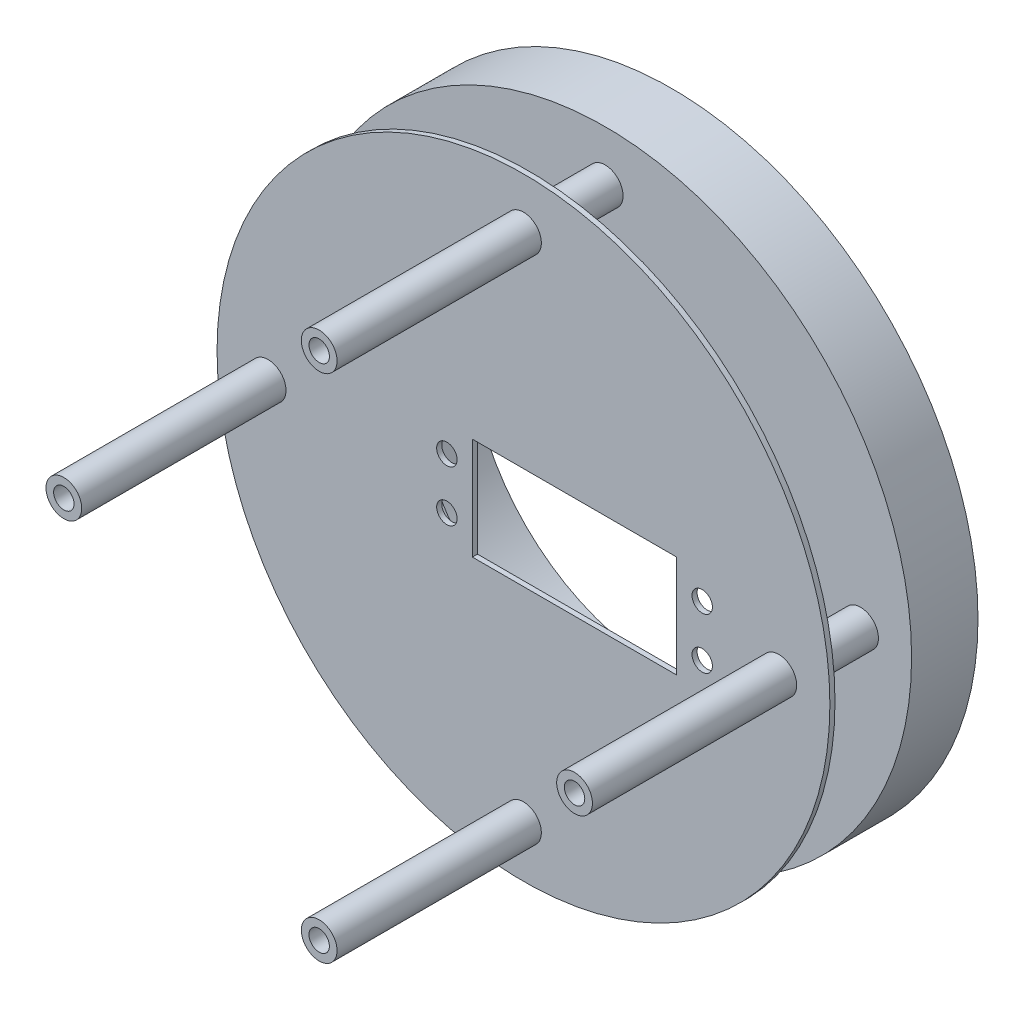
SolidWorks part; units mm, degrees
ref_plane "前视基准面" through (0, 0, 0) normal (0, 0, 1) x (1, 0, 0)
ref_plane "上视基准面" through (0, 0, 0) normal (0, 1, 0) x (1, 0, 0)
ref_plane "右视基准面" through (0, 0, 0) normal (1, 0, 0) x (0, 0, -1)
sketch "草图1" plane through (0, 0, 0) normal (0, 0, 1) x (1, 0, 0)
  circle A0 centre (0, 0) radius 60
  circle A1 centre (0, 0) radius 37.5
  dimension "D1" = 120
  dimension "D2" = 75
extrude "凸台-拉伸1" add sketch "草图1" along normal blind 13
ref_plane "基准面1" through (0, 0, 28) normal (0, 0, 1) x (1, 0, 0)
sketch "草图4" plane through (0, 0, 28) normal (0, 0, 1) x (1, 0, 0)
  line L1 (-10, 10) -> (30, 10)
  line L2 (-10, 10) -> (-10, -10)
  line L3 (-10, -10) -> (30, -10)
  line L4 (30, 10) -> (30, -10)
  circle A0 centre (0, 0) radius 60
  circle A2 centre (-15, 5) radius 2
  circle A3 centre (35, 5) radius 2
  circle A4 centre (35, -5) radius 2
  circle A5 centre (-15, -5) radius 2
  point P7 (-10, 0)
  dimension "D1" = 120
  dimension "D2" = 40
  dimension "D5" = 4
  dimension "D6" = 4
  dimension "D7" = 4
  dimension "D8" = 4
  dimension "D3" = 20
  dimension "D4" = 10
  dimension "D9" = 5
  dimension "D10" = 5
  dimension "D11" = 5
  dimension "D12" = 5
  dimension "D13" = 5
  dimension "D14" = 5
  dimension "D15" = 5
  dimension "D16" = 5
extrude "凸台-拉伸2" add sketch "草图4" along normal blind 1 separate body
sketch "草图5" plane through (0, 0, 13) normal (0, 0, 1) x (1, 0, 0)
  circle A0 centre (50, 0) radius 3.5
  circle A1 centre (0, -50) radius 3.5
  circle A2 centre (-50, 0) radius 3.5
  circle A3 centre (0, 50) radius 3.5
  point P11 (0, 0)
  dimension "D1" = 7
  dimension "D3" = 50
  dimension "D2" = 4
extrude "凸台-拉伸3" add sketch "草图5" along normal blind 56
sketch "草图6" plane through (0, 0, 69) normal (0, 0, 1) x (1, 0, 0)
  circle A0 centre (50, 0) radius 2
  circle A1 centre (0, 50) radius 2
  circle A2 centre (-50, 0) radius 2
  circle A3 centre (0, -50) radius 2
  dimension "D1" = 4
  dimension "D2" = 4
  dimension "D3" = 4
  dimension "D4" = 4
extrude "切除-拉伸1" cut sketch "草图6" against normal blind 5
sketch "草图7" plane through (0, 0, 0) normal (0, 0, -1) x (-1, 0, 0)
  circle A0 centre (0, 0) radius 45
  dimension "D1" = 90
extrude "切除-拉伸2" cut sketch "草图7" against normal blind 2
